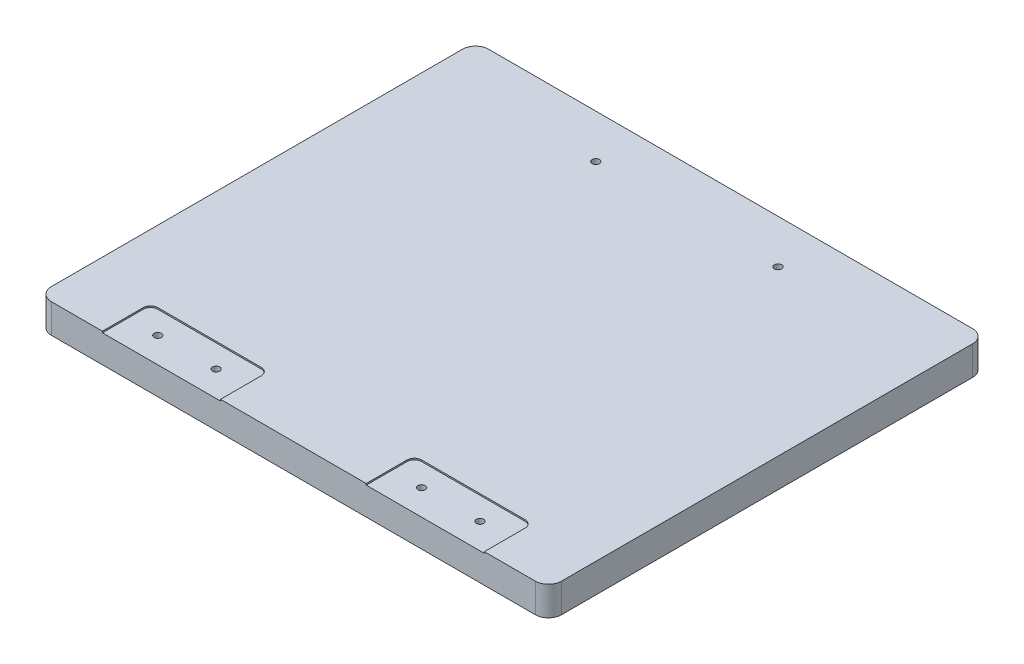
SolidWorks part; units mm, degrees
ref_plane "정면" through (0, 0, 0) normal (0, 0, 1) x (1, 0, 0)
ref_plane "윗면" through (0, 0, 0) normal (0, 1, 0) x (1, 0, 0)
ref_plane "우측면" through (0, 0, 0) normal (1, 0, 0) x (0, 0, -1)
sketch "스케치1" plane through (0, 0, 0) normal (0, 1, 0) x (1, 0, 0)
  line L1 (-175, 150) -> (175, 150)
  line L2 (-175, 150) -> (-175, -150)
  line L3 (-175, -150) -> (175, -150)
  line L4 (175, 150) -> (175, -150)
  line L5 (0, -150) -> (0, 150) construction
  line L6 (-175, 0) -> (175, 0) construction
  point P0 (0, 0)
  dimension "D1" = 350
  dimension "D2" = 300
extrude "보스-돌출1" add sketch "스케치1" along normal blind 20
fillet "필렛1" radius 9 4 edges at (175, 10, 150) (-175, 10, -150) (175, 10, -150) (-175, 10, 150)
sketch "스케치2" plane through (0, 20, 0) normal (0, 1, 0) x (1, 0, 0)
  line L0 (-166, -150) -> (166, -150) construction
  line L1 (-131, -150) -> (-50, -150)
  line L2 (-131, -150) -> (-131, -122)
  line L3 (-126, -117) -> (-55, -117)
  line L4 (-50, -150) -> (-50, -122)
  line L5 (-175, 141) -> (-175, -141) construction
  line L6 (50, -150) -> (131, -150)
  line L7 (50, -150) -> (50, -122)
  line L8 (55, -117) -> (126, -117)
  line L9 (131, -150) -> (131, -122)
  arc A0 (126, -117) -> (131, -122) centre (126, -122) cw
  arc A1 (50, -122) -> (55, -117) centre (55, -122) cw
  arc A2 (-55, -117) -> (-50, -122) centre (-55, -122) cw
  arc A3 (-131, -122) -> (-126, -117) centre (-126, -122) cw
  dimension "D6" = 5
  dimension "D1" = 44
  dimension "D2" = 81
  dimension "D3" = 100
  dimension "D4" = 81
  dimension "D5" = 33
extrude "컷-돌출1" cut sketch "스케치2" against normal blind 1
hole_wizard "M6 나사 구멍1" positions "스케치3" profile "스케치4" tap size "M6" standard "KS"
sketch "스케치3" plane through (0, 19, 0) normal (0, 1, 0) x (1, 0, 0)
  line L0 (-131, -150) -> (-50, -150) construction
  line L1 (-175, 141) -> (-175, -141) construction
  line L2 (166, 150) -> (-166, 150) construction
  point P0 (-110.5, -132.5)
  point P2 (-70.5, -132.5)
  point P4 (70.5, -132.5)
  point P6 (110.5, -132.5)
  point P13 (-62.5, 120)
  point P15 (62.5, 120)
  point P20 (0, 0)
  dimension "D1" = 17.5
  dimension "D2" = 64.5
  dimension "D3" = 40
  dimension "D4" = 40
  dimension "D5" = 141
  dimension "D6" = 112.5
  dimension "D7" = 125
  dimension "D8" = 30
sketch "스케치4" plane through (-110.5, 19, 132.5) normal (1, 0, 0) x (0, 0, 1)
  line L0 (0, 0) -> (0, 15.5022)
  line L1 (0, 15.5022) -> (2.5, 14)
  line L2 (2.5, 14) -> (2.5, 0)
  line L5 (2.5, 0) -> (0, 0)
  line L10 (0, 15.5022) -> (-2.5, 14) construction
  line L11 (0, -6.35) -> (0, 107.95) construction
  dimension "탭 드릴 지름" = 5
  dimension "탭 드릴 깊이" = 14
  dimension "드릴 각도" = 118
cosmetic thread "구멍 나사산1" parameters "D1"=10, "D2"=6
cosmetic thread "구멍 나사산2" parameters "D1"=10, "D2"=6
cosmetic thread "구멍 나사산3" parameters "D1"=10, "D2"=6
cosmetic thread "구멍 나사산4" parameters "D1"=10, "D2"=6
hole_wizard "M6 나사 구멍2" positions "스케치5" profile "스케치6" tap size "M6" standard "KS"
sketch "스케치5" plane through (0, 20, 0) normal (0, 1, 0) x (1, 0, 0)
  point P0 (-62.5, 120)
  point P3 (62.5, 120)
sketch "스케치6" plane through (-62.5, 20, -120) normal (1, 0, 0) x (0, 0, 1)
  line L0 (0, 0) -> (0, 13.5022)
  line L1 (0, 13.5022) -> (2.5, 12)
  line L2 (2.5, 12) -> (2.5, 0)
  line L5 (2.5, 0) -> (0, 0)
  line L10 (0, 13.5022) -> (-2.5, 12) construction
  line L11 (0, -6.35) -> (0, 107.95) construction
  dimension "탭 드릴 지름" = 5
  dimension "탭 드릴 깊이" = 12
  dimension "드릴 각도" = 118
cosmetic thread "구멍 나사산5" parameters "D1"=8, "D2"=6
cosmetic thread "구멍 나사산6" parameters "D1"=8, "D2"=6
